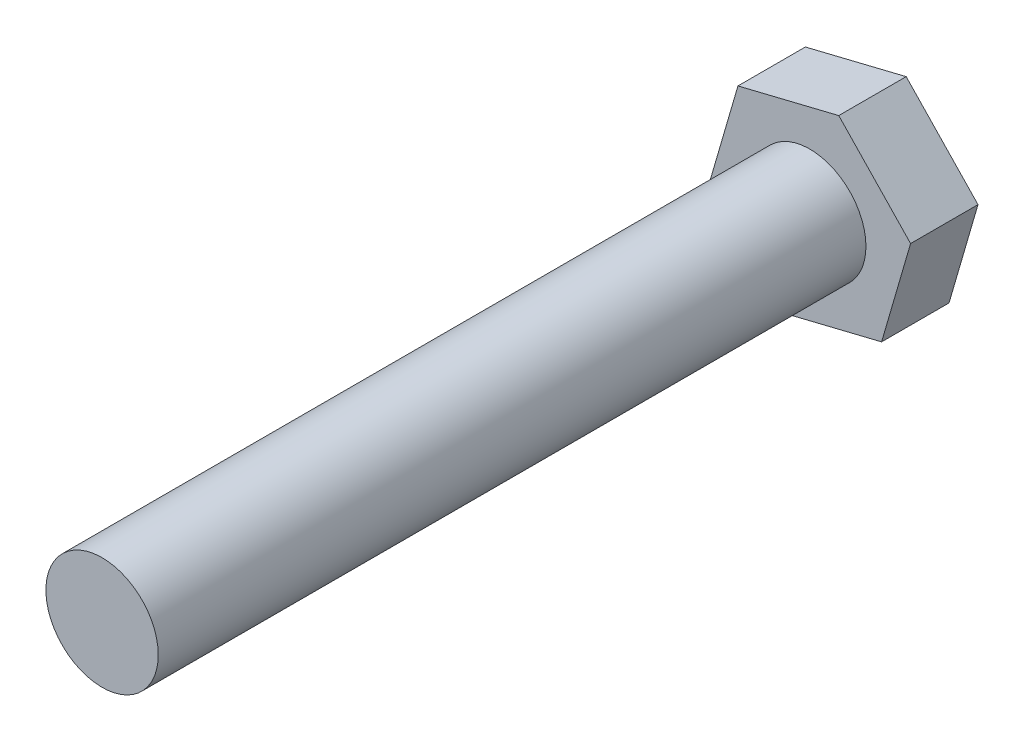
SolidWorks part; units mm, degrees
ref_plane "Front Plane" through (0, 0, 0) normal (0, 0, 1) x (1, 0, 0)
ref_plane "Top Plane" through (0, 0, 0) normal (0, 1, 0) x (1, 0, 0)
ref_plane "Right Plane" through (0, 0, 0) normal (1, 0, 0) x (0, 0, -1)
sketch "Sketch1" plane through (0, 0, 0) normal (0, 0, 1) x (1, 0, 0)
  line L1 (-3.1958, 3.3347) -> (-4.4858, -1.1003)
  line L2 (-4.4858, -1.1003) -> (-1.2901, -4.435)
  line L3 (-1.2901, -4.435) -> (3.1958, -3.3347)
  line L4 (3.1958, -3.3347) -> (4.4858, 1.1003)
  line L5 (4.4858, 1.1003) -> (1.2901, 4.435)
  line L6 (1.2901, 4.435) -> (-3.1958, 3.3347)
  circle A0 centre (0, 0) radius 4 construction
  dimension "D1" = 8
extrude "Boss-Extrude1" add sketch "Sketch1" along normal blind 3
sketch "Sketch2" plane through (0, 0, 3) normal (0, 0, 1) x (1, 0, 0)
  circle A0 centre (0, 0) radius 2.5
  dimension "D1" = 5
extrude "Boss-Extrude2" add sketch "Sketch2" along normal blind 31.492
